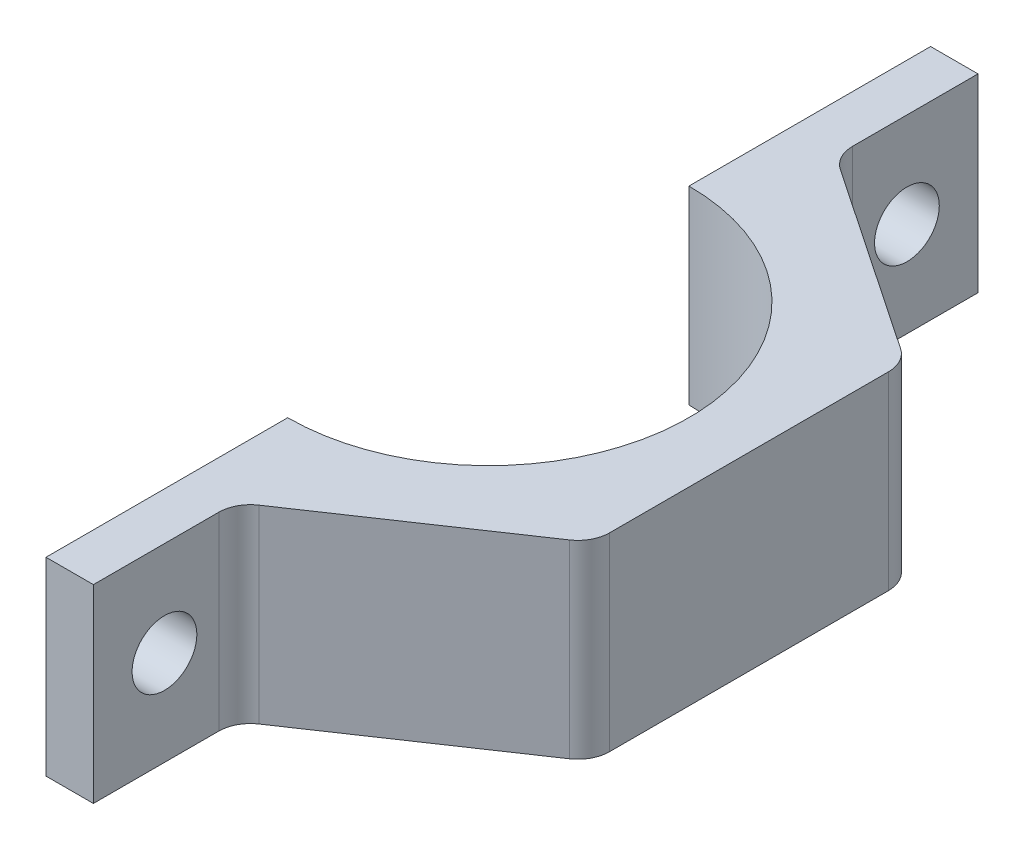
SolidWorks part; units mm, degrees
ref_plane "Front Plane" through (0, 0, 0) normal (0, 0, 1) x (1, 0, 0)
ref_plane "Top Plane" through (0, 0, 0) normal (0, 1, 0) x (1, 0, 0)
ref_plane "Right Plane" through (0, 0, 0) normal (1, 0, 0) x (0, 0, -1)
sketch "Sketch1" plane through (0, 0, 0) normal (0, 1, 0) x (1, 0, 0)
  line L0 (0, 28) -> (0, 12.7)
  line L1 (0, 28) -> (3, 28)
  line L2 (3, 28) -> (3, 20.0629)
  line L3 (-30.2627, 0) -> (28.7382, 0) construction
  line L4 (16.5002, 8.8235) -> (16.5002, -8.8235)
  line L5 (15.6192, 10.4812) -> (3.881, 18.4053)
  line L6 (15.6192, -10.4812) -> (3.881, -18.4053)
  line L7 (3, -28) -> (3, -20.0629)
  line L8 (0, -28) -> (3, -28)
  line L9 (0, -12.7) -> (0, -28)
  arc A0 (0, -12.7) -> (0, 12.7) centre (0, 0) ccw
  arc A1 (3.3432, 18.9426) -> (0, 19.2354) centre (0, 0) ccw
  arc A2 (16.5002, 8.8235) -> (15.6192, 10.4812) centre (14.5002, 8.8235) ccw
  arc A3 (3, 20.0629) -> (3.881, 18.4053) centre (5, 20.0629) ccw
  arc A4 (3, -20.0629) -> (3.881, -18.4053) centre (5, -20.0629) cw
  arc A5 (16.5002, -8.8235) -> (15.6192, -10.4812) centre (14.5002, -8.8235) cw
  arc A6 (0, -19.2354) -> (3.3432, -18.9426) centre (0, 0) ccw
  point P6 (0, 0)
  point P14 (16.5002, 0)
  point P15 (16.5002, 9.8865)
  point P16 (16.5002, 9.8865)
  point P18 (16.5002, 9.8865)
  point P21 (3, 19)
  point P23 (16.5002, 0)
  point P29 (3, -19)
  point P30 (16.5002, -9.8865)
  dimension "D1" = 25.4
  dimension "D5" = 2
  dimension "D6" = 2
  dimension "D2" = 56
  dimension "D3" = 3
  dimension "D4" = 9
extrude "Boss-Extrude1" add sketch "Sketch1" along normal blind 12 contours A0 L3 L4 A2 L5 A3 A1 L0 | A3 L2 L1 L0 A1 | L3 A0 L9 A6 A4 L6 A5 L4 | A6 L9 L8 L7 A4
sketch "Sketch2" plane through (3, 0, 0) normal (1, 0, 0) x (0, 0, -1)
  line L0 (28, 12) -> (28, 0) construction
  line L1 (0, 0) -> (0, 14.8973) construction
  circle A0 centre (23.5, 6) radius 2.05
  circle A1 centre (-23.5, 6) radius 2.05
  dimension "D1" = 4.1
  dimension "D2" = 4.5
extrude "Cut-Extrude1" cut sketch "Sketch2" against normal blind 12
